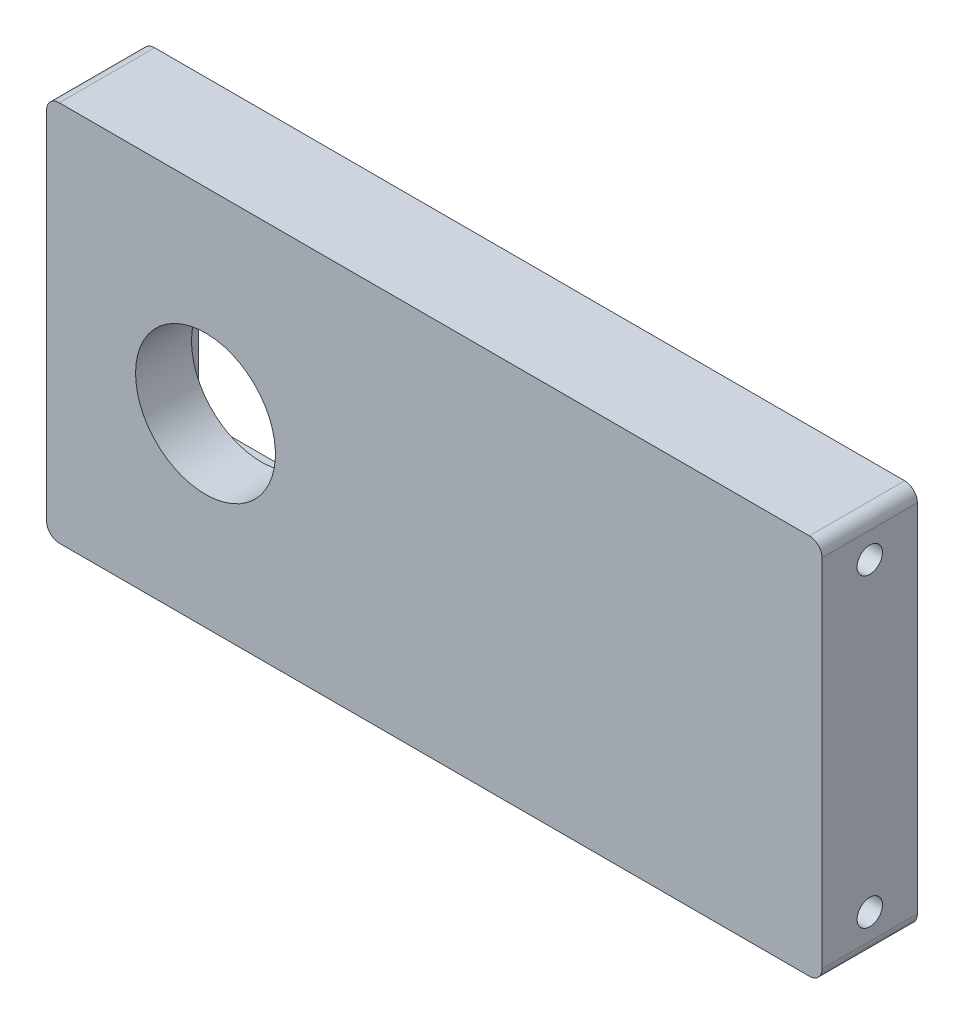
SolidWorks part; units mm, degrees
material "Cedar"
ref_plane "Plan de face" through (0, 0, 0) normal (0, 0, 1) x (1, 0, 0)
ref_plane "Plan de dessus" through (0, 0, 0) normal (0, 1, 0) x (1, 0, 0)
ref_plane "Plan de droite" through (0, 0, 0) normal (1, 0, 0) x (0, 0, -1)
sketch "Sketch1" plane through (0, 0, 0) normal (0, 0, 1) x (1, 0, 0)
  line L1 (-59, 30) -> (59, 30)
  line L2 (-61, 28) -> (-61, -28)
  line L3 (-59, -30) -> (59, -30)
  line L4 (61, 28) -> (61, -28)
  line L5 (-61, 30) -> (61, -30) construction
  line L6 (-61, -30) -> (61, 30) construction
  arc A0 (59, 30) -> (61, 28) centre (59, 28) cw
  arc A1 (59, -30) -> (61, -28) centre (59, -28) ccw
  arc A2 (-61, -28) -> (-59, -30) centre (-59, -28) ccw
  arc A3 (-59, 30) -> (-61, 28) centre (-59, 28) ccw
  point P0 (0, 0)
  dimension "D3" = 2
  dimension "D1" = 122
  dimension "D2" = 60
extrude "Boss-Extrude1" add sketch "Sketch1" along normal mid plane 15
sketch "Sketch2" plane through (61, 0, 0) normal (1, 0, 0) x (0, 0, -1)
  line L0 (0, 0) -> (0, 24) construction
  line L1 (-12.254, 0) -> (18.0308, 0) construction
  circle A0 centre (0, 24) radius 2
  circle A1 centre (0, -24) radius 2
  dimension "D2" = 4
  dimension "D1" = 24
extrude "Cut-Extrude1" cut sketch "Sketch2" against normal blind 15
sketch "Sketch3" plane through (0, 0, -7.5) normal (0, 0, -1) x (-1, 0, 0)
  line L1 (61, 28) -> (61, -28) construction
  circle A0 centre (36, -0.8508) radius 11
  dimension "D1" = 22
  dimension "D2" = 25
extrude "Cut-Extrude3" cut sketch "Sketch3" against normal blind 35 contours A0
sketch "Sketch4" plane through (0, 0, 7.5) normal (0, 0, 1) x (1, 0, 0)
  line L0 (61, -28) -> (61, 28) construction
  circle A0 centre (32.5, 0) radius 6
  dimension "D2" = 12
  dimension "D1" = 28.5
extrude "Cut-Extrude4" [suppressed] cut sketch "Sketch4" against normal blind 19.95
sketch "Sketch6" plane through (0, 0, -7.5) normal (0, 0, -1) x (-1, 0, 0)
  line L0 (49.1, 15.2492) -> (52.1, 12.2492)
  line L1 (22.9, 15.2492) -> (49.1, 15.2492)
  line L2 (19.9, 12.2492) -> (19.9, -13.9508)
  line L3 (22.9, -16.9508) -> (49.1, -16.9508)
  line L4 (52.1, 12.2492) -> (52.1, -13.9508)
  line L5 (19.9, 15.2492) -> (52.1, -16.9508) construction
  line L6 (19.9, -16.9508) -> (52.1, 15.2492) construction
  line L7 (52.1, -13.9508) -> (49.1, -16.9508)
  line L8 (19.9, -13.9508) -> (22.9, -16.9508)
  line L9 (22.9, 15.2492) -> (19.9, 12.2492)
  point P0 (36, -0.8508)
  dimension "D1" = 32.2
extrude "Cut-Extrude5" cut sketch "Sketch6" against normal blind 6.2
